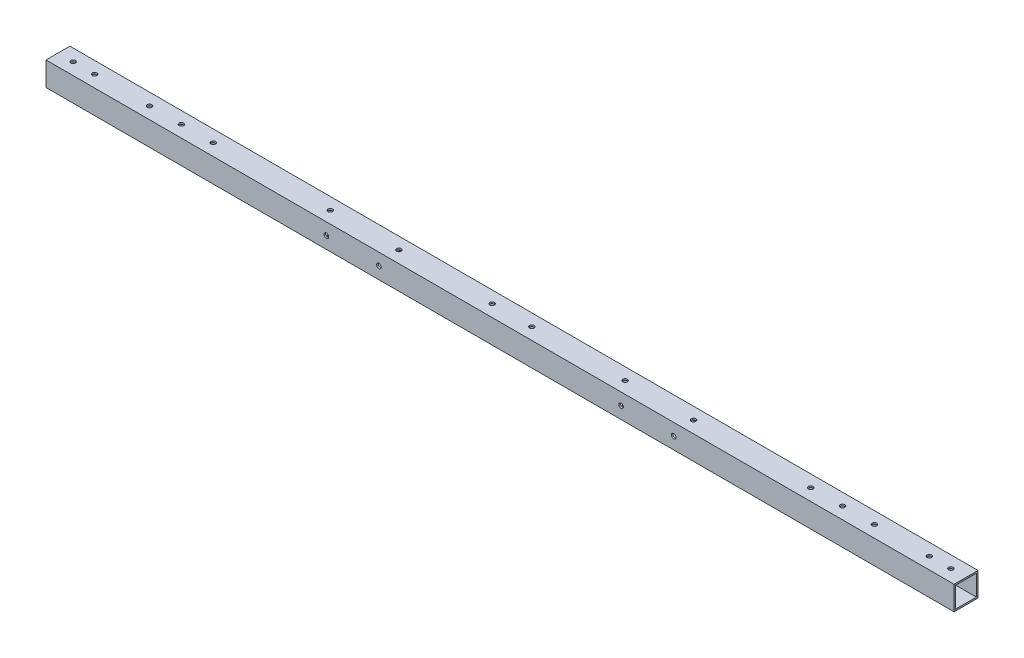
SolidWorks part; units mm, degrees
material "Thornel Mat VMA"
ref_plane "前视基准面" through (0, 0, 0) normal (0, 0, 1) x (1, 0, 0)
ref_plane "上视基准面" through (0, 0, 0) normal (0, 1, 0) x (1, 0, 0)
ref_plane "右视基准面" through (0, 0, 0) normal (1, 0, 0) x (0, 0, -1)
other "Configuration Table"
sketch "草图1" plane through (0, 0, 0) normal (1, 0, 0) x (0, 0, -1)
  line L0 (-6.5, -6.5) -> (-6.5, 6.5)
  line L1 (-7.5, -7.5) -> (7.5, -7.5)
  line L2 (-7.5, -7.5) -> (-7.5, 7.5)
  line L3 (-7.5, 7.5) -> (7.5, 7.5)
  line L4 (7.5, -7.5) -> (7.5, 7.5)
  line L5 (-7.5, -7.5) -> (7.5, 7.5) construction
  line L6 (-7.5, 7.5) -> (7.5, -7.5) construction
  line L7 (-6.5, 6.5) -> (6.5, 6.5)
  line L8 (6.5, -6.5) -> (6.5, 6.5)
  line L9 (-6.5, -6.5) -> (6.5, -6.5)
  point P0 (0, 0)
  dimension "D1" = 15
  dimension "D2" = 15
  dimension "D3" = 1
extrude "凸台-拉伸1" add sketch "草图1" along normal blind 570
sketch "草图2" plane through (0, 7.5, 0) normal (0, 1, 0) x (1, 0, 0)
  circle A0 centre (560.5, 0) radius 1.45 construction
  circle A1 centre (547, 0) radius 1.45 construction
  circle A2 centre (399, 0) radius 1.45 construction
  circle A3 centre (356, 0) radius 1.45 construction
  circle A4 centre (214, 0) radius 1.45 construction
  circle A5 centre (171, 0) radius 1.45 construction
  circle A6 centre (23, 0) radius 1.45 construction
  circle A7 centre (9.5, 0) radius 1.45 construction
  circle A8 centre (560.5, 0) radius 1.45
  circle A9 centre (547, 0) radius 1.45
  circle A10 centre (399, 0) radius 1.45
  circle A11 centre (356, 0) radius 1.45
  circle A12 centre (214, 0) radius 1.45
  circle A13 centre (171, 0) radius 1.45
  circle A14 centre (23, 0) radius 1.45
  circle A15 centre (9.5, 0) radius 1.45
  circle A16 centre (57.5, 0) radius 1.45 construction
  circle A17 centre (472.5, 0) radius 1.45
  circle A18 centre (472.5, 0) radius 1.45
  circle A19 centre (77.5, 0) radius 1.45 construction
  circle A20 centre (492.5, 0) radius 1.45 construction
  circle A21 centre (512.5, 0) radius 1.45 construction
  circle A22 centre (57.5, 0) radius 1.45
  circle A23 centre (77.5, 0) radius 1.45
  circle A24 centre (492.5, 0) radius 1.45
  circle A25 centre (512.5, 0) radius 1.45
  circle A26 centre (272.5, 0) radius 1.45 construction
  circle A27 centre (297.5, 0) radius 1.45 construction
  circle A28 centre (272.5, 0) radius 1.45
  circle A29 centre (297.5, 0) radius 1.45
  circle A30 centre (97.5, 0) radius 1.45 construction
  circle A31 centre (97.5, 0) radius 1.45
  dimension "D1" = 0
extrude "切除-拉伸1" cut sketch "草图2" against normal through all
sketch "草图3" plane through (0, 0, -7.5) normal (0, 0, -1) x (-1, 0, 0)
  circle A0 centre (-176, 0) radius 1.45 construction
  circle A1 centre (-209, 0) radius 1.45 construction
  circle A2 centre (-361, 0) radius 1.45 construction
  circle A3 centre (-394, 0) radius 1.45 construction
  circle A4 centre (-176, 0) radius 1.45
  circle A5 centre (-209, 0) radius 1.45
  circle A6 centre (-361, 0) radius 1.45
  circle A7 centre (-394, 0) radius 1.45
extrude "切除-拉伸2" cut sketch "草图3" against normal through all
